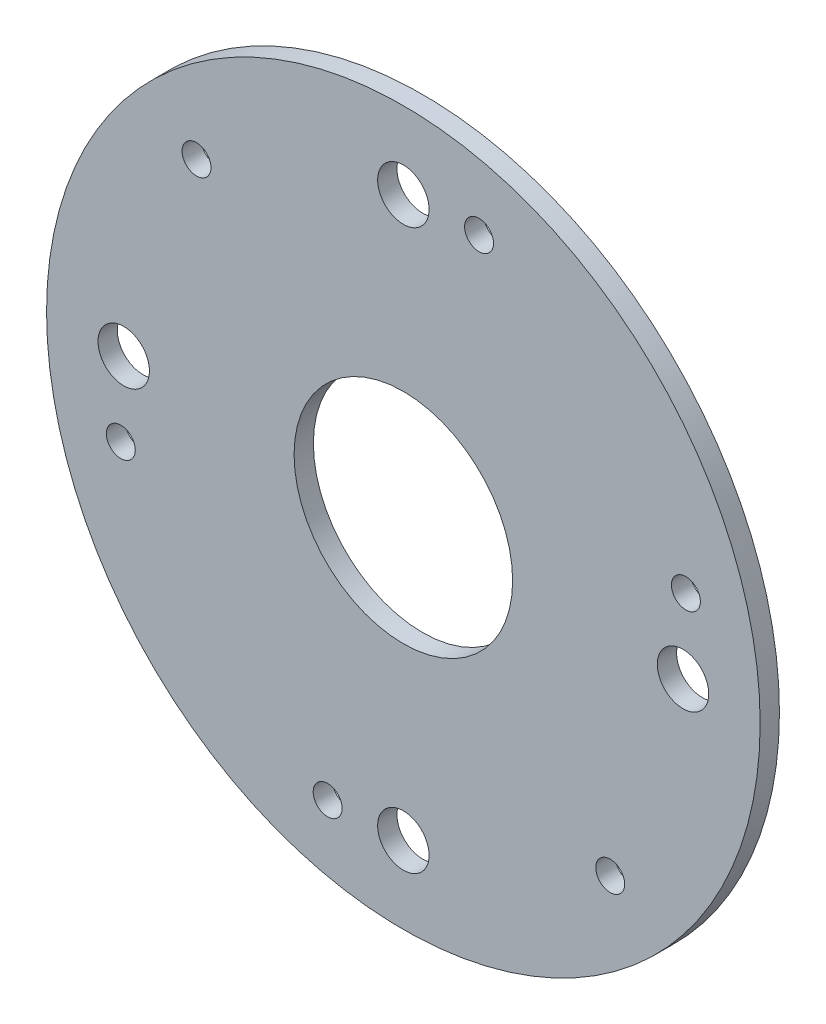
SolidWorks part; units mm, degrees
ref_plane "Спереди" through (0, 0, 0) normal (0, 0, 1) x (1, 0, 0)
ref_plane "Сверху" through (0, 0, 0) normal (0, 1, 0) x (1, 0, 0)
ref_plane "Справа" through (0, 0, 0) normal (1, 0, 0) x (0, 0, -1)
sketch "Эскиз1" plane through (0, 0, 0) normal (0, 0, 1) x (1, 0, 0)
  circle A0 centre (0, 0) radius 55.5
  circle A1 centre (0, 0) radius 17
extrude "Carrier_front" add sketch "Эскиз1" along normal blind 3 from offset 44.5
sketch "Эскиз2" plane through (0, 0, 0) normal (0, 0, 1) x (1, 0, 0)
  circle A0 centre (43.5, 0) radius 2.25
  circle A1 centre (0, 43.5) radius 2.25
  circle A2 centre (-43.5, 0) radius 2.25
  circle A3 centre (0, -43.5) radius 2.25
  circle A4 centre (43.9496, 11.7763) radius 2.25
  circle A5 centre (11.7763, 43.9496) radius 2.25
  circle A6 centre (-32.1734, 32.1734) radius 2.25
  circle A7 centre (-43.9496, -11.7763) radius 2.25
  circle A8 centre (-11.7763, -43.9496) radius 2.25
  circle A9 centre (32.1734, -32.1734) radius 2.25
extrude "Through_holes" cut sketch "Эскиз2" against normal mid plane 200
sketch "Эскиз3" plane through (0, 0, 0) normal (0, 0, 1) x (1, 0, 0)
  circle A0 centre (43.5, 0) radius 4
  circle A1 centre (0, 43.5) radius 4
  circle A2 centre (-43.5, 0) radius 4
  circle A3 centre (0, -43.5) radius 4
extrude "Вырез-Вытянуть2" cut sketch "Эскиз3" against normal mid plane 200
